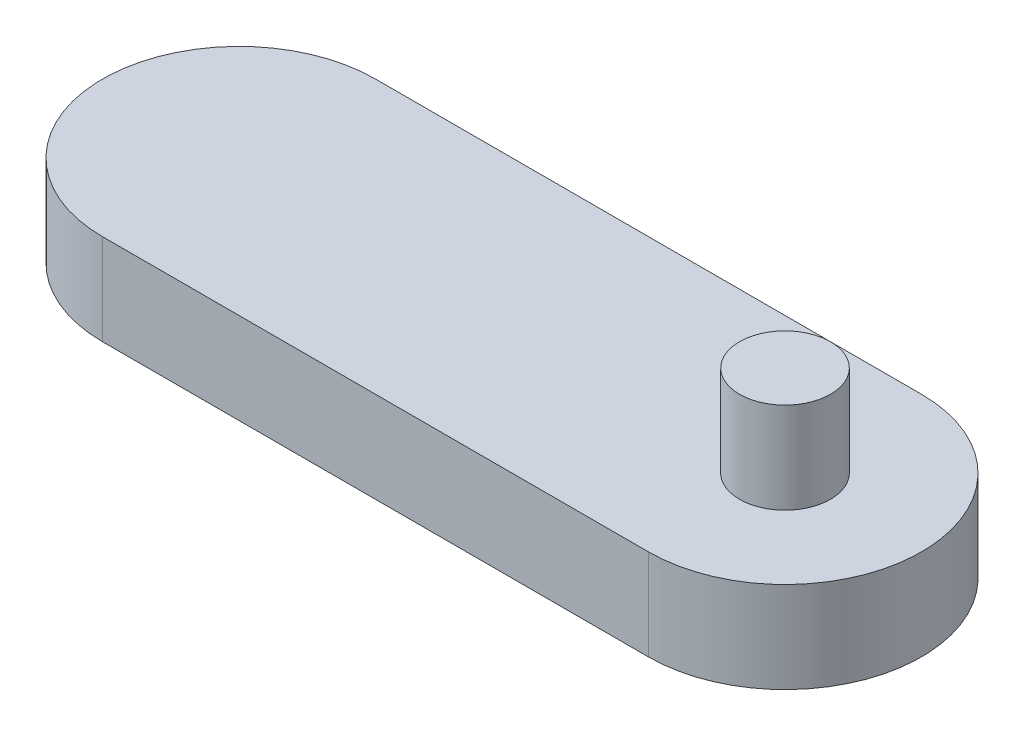
SolidWorks part; units mm, degrees
ref_plane "Front Plane" through (0, 0, 0) normal (0, 0, 1) x (1, 0, 0)
ref_plane "Top Plane" through (0, 0, 0) normal (0, 1, 0) x (1, 0, 0)
ref_plane "Right Plane" through (0, 0, 0) normal (1, 0, 0) x (0, 0, -1)
sketch "Sketch1" plane through (0, 0, 0) normal (0, 1, 0) x (1, 0, 0)
  line L0 (-152.4, 0) -> (152.4, 0) construction
  line L1 (-152.4, 76.2) -> (152.4, 76.2)
  line L2 (-152.4, -76.2) -> (152.4, -76.2)
  arc A0 (-152.4, 76.2) -> (-152.4, -76.2) centre (-152.4, 0) ccw
  arc A1 (152.4, -76.2) -> (152.4, 76.2) centre (152.4, 0) ccw
  point P2 (0, 0)
extrude "link1" add sketch "Sketch1" along normal blind 50.8
sketch "Sketch2" plane through (0, 0, 0) normal (0, -1, 0) x (1, 0, 0)
  circle A0 centre (-152.4, 0) radius 50.8
extrude "bottomcut" cut sketch "Sketch2" against normal blind 25.4
sketch "Sketch3" plane through (0, 50.8, 0) normal (0, 1, 0) x (1, 0, 0)
  circle A0 centre (152.4, 0) radius 25.4
extrude "Boss-Extrude1" add sketch "Sketch3" along normal blind 50.8
